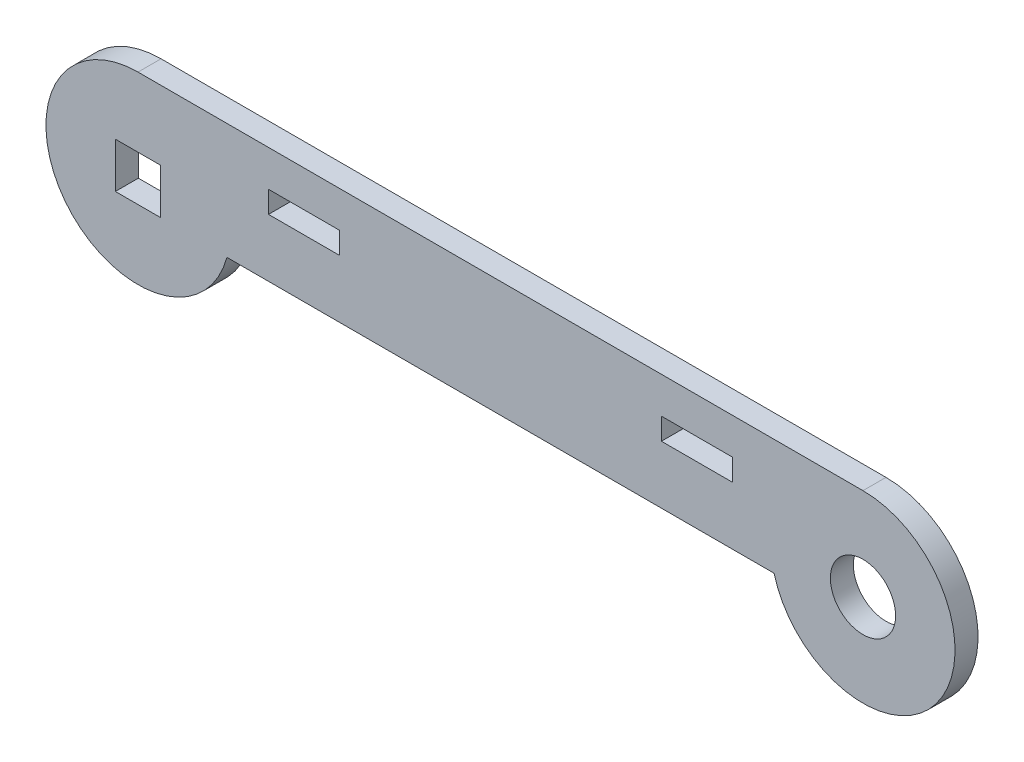
SolidWorks part; units mm, degrees
material "Acrylic (Medium-high impact)"
ref_plane "Front Plane" through (0, 0, 0) normal (0, 0, 1) x (1, 0, 0)
ref_plane "Top Plane" through (0, 0, 0) normal (0, 1, 0) x (1, 0, 0)
ref_plane "Right Plane" through (0, 0, 0) normal (1, 0, 0) x (0, 0, -1)
sketch "Sketch1" plane through (0, 0, 0) normal (0, 0, 1) x (1, 0, 0)
  line L0 (0, 0) -> (50, 0) construction
  line L1 (-1.5625, -1.5625) -> (1.5625, -1.5625)
  line L2 (-1.5625, -1.5625) -> (-1.5625, 1.5625)
  line L3 (-1.5625, 1.5625) -> (1.5625, 1.5625)
  line L4 (1.5625, -1.5625) -> (1.5625, 1.5625)
  line L5 (-1.5625, -1.5625) -> (1.5625, 1.5625) construction
  line L6 (-1.5625, 1.5625) -> (1.5625, -1.5625) construction
  line L7 (0, 6.35) -> (50, 6.35)
  line L8 (6.1319, -1.65) -> (43.8681, -1.65)
  line L9 (25, 6.35) -> (25, -1.65) construction
  line L10 (9, 2.35) -> (13.9, 2.35)
  line L11 (9, 2.35) -> (9, 3.85)
  line L12 (9, 3.85) -> (13.9, 3.85)
  line L13 (13.9, 2.35) -> (13.9, 3.85)
  line L14 (41, 2.35) -> (36.1, 2.35)
  line L15 (36.1, 2.35) -> (36.1, 3.85)
  line L16 (41, 2.35) -> (41, 3.85)
  line L17 (41, 3.85) -> (36.1, 3.85)
  circle A0 centre (0, 0) radius 6.35
  circle A1 centre (50, 0) radius 6.35
  circle A2 centre (50, 0) radius 2.25
  circle A3 centre (0, 0) radius 8 construction
  dimension "D4" = 4.5
  dimension "D6" = 1.5
  dimension "D8" = 16
  dimension "D2" = 3.125
  dimension "D3" = 3.125
  dimension "D1" = 50
  dimension "D5" = 8
  dimension "D7" = 4.9
  dimension "D9" = 2.5
  dimension "D10" = 9
extrude "Boss-Extrude1" add sketch "Sketch1" along normal blind 1.5875
